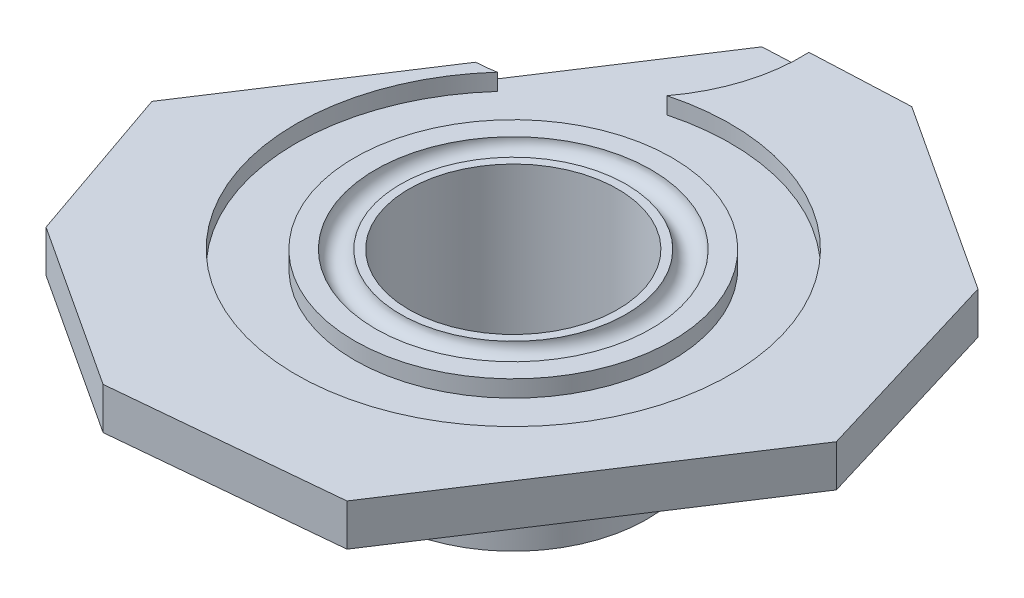
SolidWorks part; units mm, degrees
ref_plane "Спереди" through (0, 0, 0) normal (0, 0, 1) x (1, 0, 0)
ref_plane "Сверху" through (0, 0, 0) normal (0, 1, 0) x (1, 0, 0)
ref_plane "Справа" through (0, 0, 0) normal (1, 0, 0) x (0, 0, -1)
sketch "Эскиз1" plane through (0, 0, 0) normal (0, 1, 0) x (1, 0, 0)
  circle A0 centre (0, 0) radius 12.5
  circle A1 centre (0, 0) radius 40
extrude "Вытянуть1" add sketch "Эскиз1" along normal blind 20
sketch "Эскиз4" plane through (0, 20, 0) normal (0, 1, 0) x (1, 0, 0)
  circle A0 centre (0, 0) radius 15
sketch "Эскиз6" plane through (0, 0, 0) normal (1, 0, 0) x (0, 0, -1)
  line L0 (15, 20) -> (-15, 20) construction
  line L1 (40, 20) -> (-40, 20) construction
  circle A0 centre (-15, 20) radius 1.5
ref_plane "Плоскость1" through (0, 14.5, 0) normal (0, 1, 0) x (-1, 0, 0)
sweep "Вырез-По траектории3" cut profiles "Эскиз6" path "Эскиз4"
sketch "Эскиз12" plane through (0, 0, 0) normal (0, -1, 0) x (1, 0, 0)
  circle A0 centre (0, 0) radius 43.0163
  circle A1 centre (0, 0) radius 16
extrude "Вытянуть5" cut sketch "Эскиз12" against normal blind 15
fillet "Скругление2" radius 5 1 edges at (0, 15, -16)
sketch "Эскиз14" plane through (0, 20, 0) normal (0, 1, 0) x (1, 0, 0)
  circle A0 centre (0, 0) radius 19
  circle A1 centre (0, 0) radius 26
extrude "Вырез-Вытянуть3" cut sketch "Эскиз14" against normal blind 2
sketch "Эскиз15" plane through (0, 20, 0) normal (0, 1, 0) x (1, 0, 0)
  arc A0 (-27.2973, 17.6273) -> (-35.7168, 21.8543) centre (-22.7595, 37.1643) ccw
  arc A1 (-35.7168, 21.8543) -> (-27.2973, 17.6273) centre (-33.4094, 15.9518) ccw
extrude "Вырез-Вытянуть4" cut sketch "Эскиз15" against normal blind 2
sketch "Эскиз16" plane through (0, 20, 0) normal (0, 1, 0) x (1, 0, 0)
  line L0 (-8.1039, 37.8663) -> (9.0621, 38.6369)
  line L1 (-10.5432, -38.5576) -> (16.1384, -36.0485)
  line L2 (16.1384, -36.0485) -> (39.2881, -0.6149)
  line L3 (39.2881, -0.6149) -> (31.9335, 23.6944)
  line L4 (31.9335, 23.6944) -> (9.0621, 38.6369)
  line L5 (-10.5432, -38.5576) -> (-30.2604, -25.6758)
  line L6 (-7.1915, -44.52) -> (-37.8812, -24.4696)
  line L7 (-37.8812, -24.4696) -> (-45.367, 5.3714)
  line L8 (-45.367, 5.3714) -> (-23.143, 39.388)
  line L9 (-23.143, 39.388) -> (7.6403, 44.5959)
  line L10 (37.7704, 24.9111) -> (7.6403, 44.5959)
  line L11 (0, 0) -> (36.6838, 56.1494) construction
  line L12 (45.4344, -5.233) -> (37.7704, 24.9111)
  line L13 (-36.9589, -6.2971) -> (-8.1039, 37.8663)
  line L14 (-30.2604, -25.6758) -> (-36.9589, -6.2971)
  line L15 (23.1156, -39.3926) -> (45.4344, -5.233)
  line L16 (-7.1915, -44.52) -> (23.1156, -39.3926)
  line L17 (-30.2604, -25.6758) -> (-51.2226, 34.9676) construction
extrude "Вырез-Вытянуть5" cut sketch "Эскиз16" against normal blind 10
